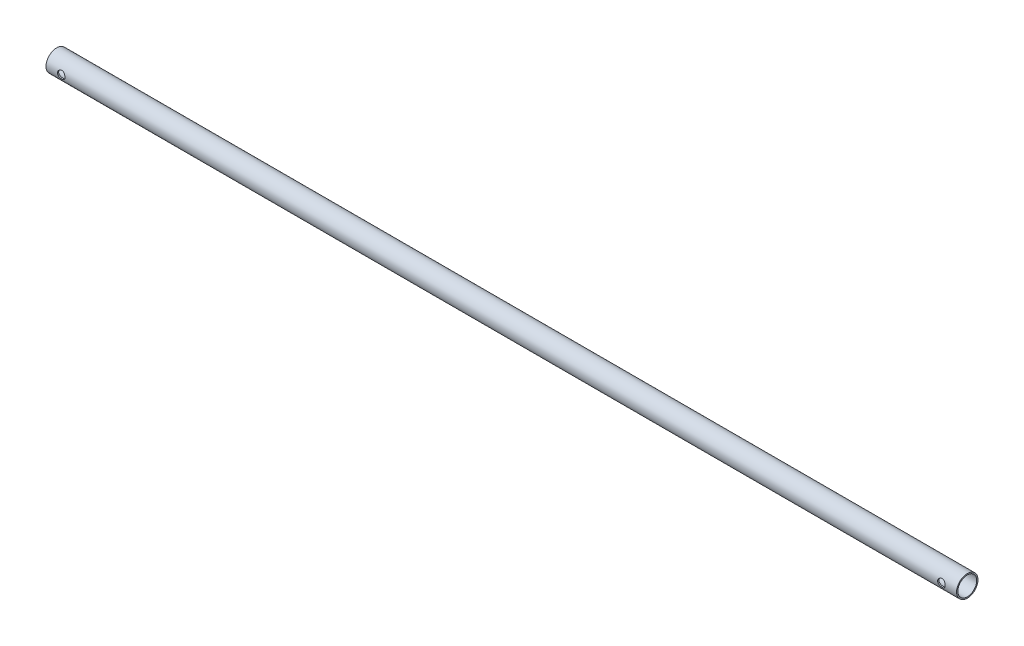
SolidWorks part; units mm, degrees
material "Galvanized Steel"
ref_plane "Front Plane" through (0, 0, 0) normal (0, 0, 1) x (1, 0, 0)
ref_plane "Top Plane" through (0, 0, 0) normal (0, 1, 0) x (1, 0, 0)
ref_plane "Right Plane" through (0, 0, 0) normal (1, 0, 0) x (0, 0, -1)
sketch "Sketch1" plane through (0, 0, 0) normal (1, 0, 0) x (0, 0, -1)
  circle A0 centre (0, 0) radius 7.8994
  circle A1 centre (0, 0) radius 8.9662
  dimension "D1" = 15.7988
  dimension "D2" = 17.9324
extrude "Boss-Extrude1" add sketch "Sketch1" along normal blind 762
sketch "Sketch2" plane through (0, 0, 0) normal (0, 0, 1) x (1, 0, 0)
  line L1 (762, -8.9662) -> (762, 8.9662) construction
  line L2 (0, 8.9662) -> (0, -8.9662) construction
  circle A0 centre (749.3, 0) radius 3.175
  circle A1 centre (12.7, 0) radius 3.175
  dimension "D1" = 12.7
  dimension "D2" = 12.7
extrude "Cut-Extrude1" cut sketch "Sketch2" against normal through all and the other way through all
